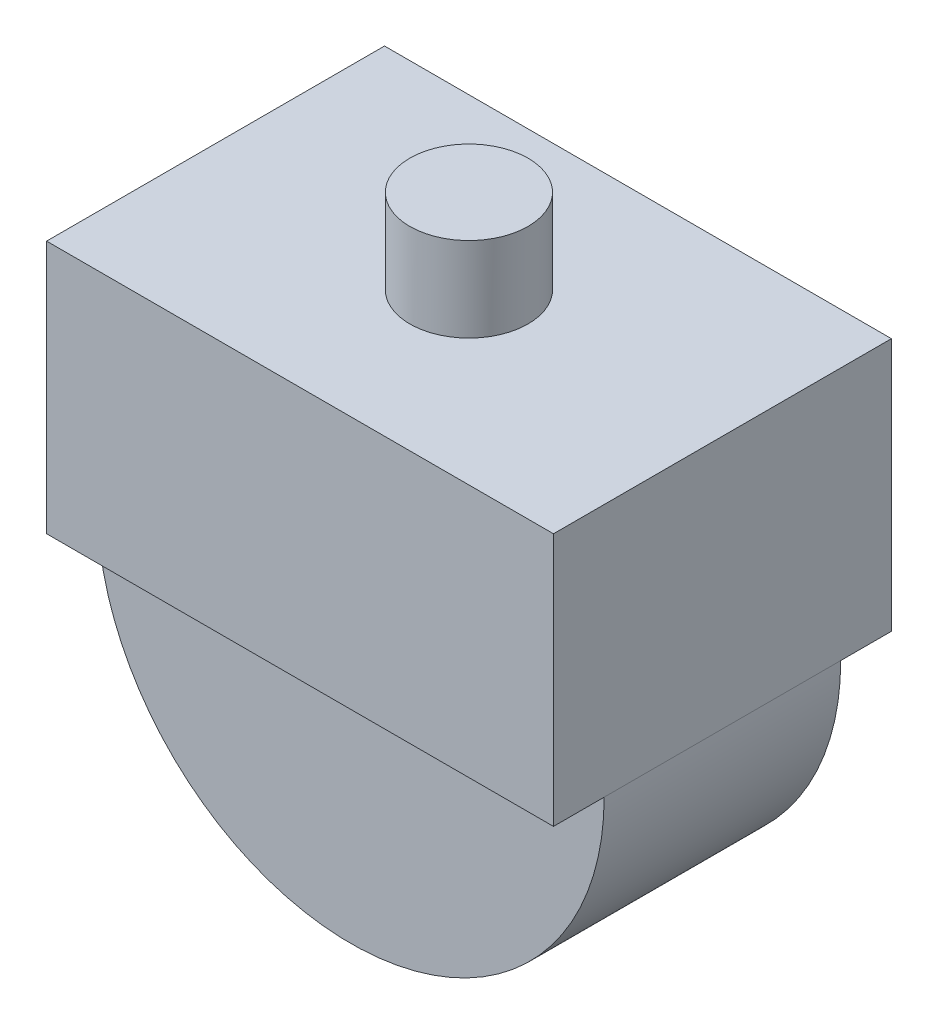
SolidWorks part; units mm, degrees
ref_plane "Plan de face" through (0, 0, 0) normal (0, 0, 1) x (1, 0, 0)
ref_plane "Plan de dessus" through (0, 0, 0) normal (0, 1, 0) x (1, 0, 0)
ref_plane "Plan de droite" through (0, 0, 0) normal (1, 0, 0) x (0, 0, -1)
sketch "Esquisse1" plane through (0, 0, 0) normal (0, 0, 1) x (1, 0, 0)
  line L0 (0, 66.7881) -> (0, 0) construction
  line L2 (15, 15) -> (-15, 15)
  line L3 (15, 15) -> (15, 0)
  line L5 (-15, 15) -> (-15, 0)
  arc A0 (-15, 0) -> (15, 0) centre (0, 0) ccw
  dimension "D1" = 30
  dimension "D2" = 15
  dimension "D3" = 15
  dimension "D4" = 15
extrude "Extrusion1" add sketch "Esquisse1" along normal blind 14
sketch "Esquisse2" plane through (0, 0, 14) normal (0, 0, 1) x (1, 0, 0)
  line L1 (15, 15) -> (-15, 15)
  line L2 (15, 15) -> (15, 0)
  line L3 (15, 0) -> (-15, 0)
  line L4 (-15, 15) -> (-15, 0)
extrude "Extrusion2" add sketch "Esquisse2" along normal blind 3
sketch "Esquisse3" plane through (0, 0, 0) normal (0, 0, -1) x (-1, 0, 0)
  line L1 (15, 15) -> (-15, 15)
  line L2 (15, 15) -> (15, 0)
  line L3 (15, 0) -> (-15, 0)
  line L4 (-15, 15) -> (-15, 0)
extrude "Extrusion3" add sketch "Esquisse3" along normal blind 3
sketch "Esquisse4" plane through (0, 15, 0) normal (0, 1, 0) x (1, 0, 0)
  line L0 (-0.0043, -7) -> (15, -7) construction
  line L1 (15, -17) -> (15, 3) construction
  circle A0 centre (-0.0043, -7) radius 3.5
  dimension "D1" = 7
extrude "Extrusion4" add sketch "Esquisse4" along normal blind 5
sketch "Esquisse5" plane through (0, 0, 14) normal (0, 0, 1) x (1, 0, 0)
  line L0 (-2.9928, 0) -> (2.9928, 0)
  arc A0 (-2.9928, 0) -> (2.9928, 0) centre (0, 0) ccw
extrude "Enlèv. mat.-Extru.1" cut sketch "Esquisse5" against normal blind 18
